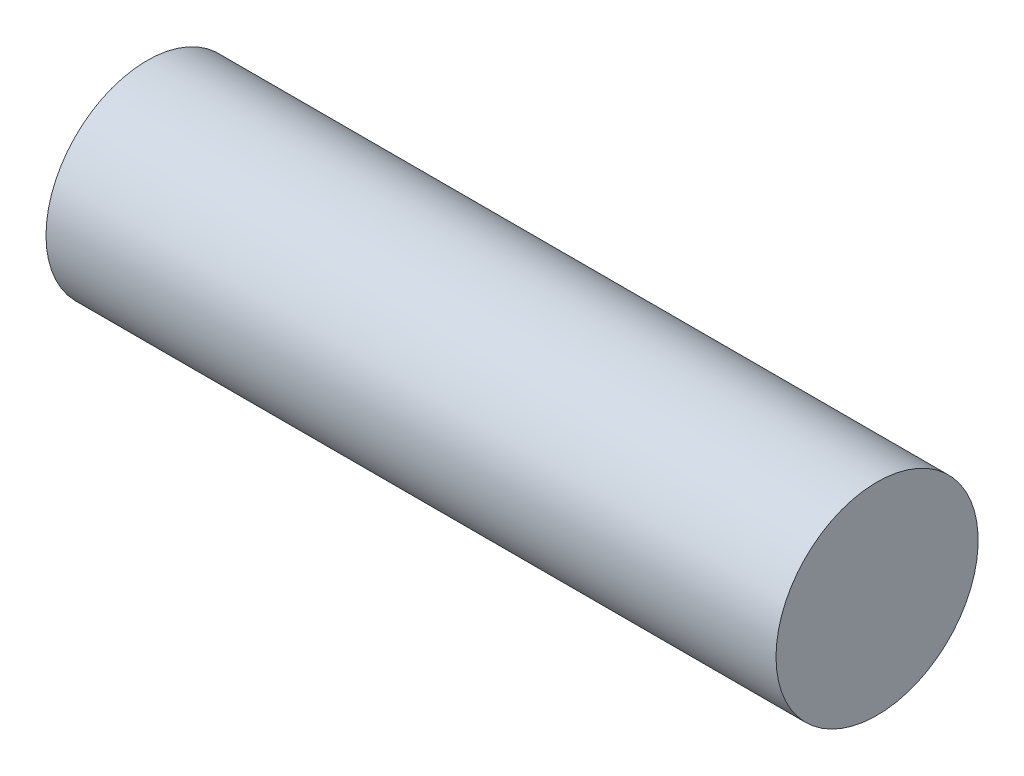
SolidWorks part; units mm, degrees
ref_plane "Front" through (0, 0, 0) normal (0, 0, 1) x (1, 0, 0)
ref_plane "Top" through (0, 0, 0) normal (0, 1, 0) x (1, 0, 0)
ref_plane "Right" through (0, 0, 0) normal (1, 0, 0) x (0, 0, -1)
sketch "Эскиз1" plane through (0, 0, 0) normal (0, 1, 0) x (1, 0, 0)
  line L0 (-39, 0) -> (43.5676, 0) construction
  line L2 (-31.6216, 0) -> (33.3784, 0)
  line L3 (-31.6216, 0) -> (-31.6216, 9)
  line L4 (-31.6216, 9) -> (33.3784, 9)
  line L5 (33.3784, 0) -> (33.3784, 9)
  dimension "D1" = 65
  dimension "D2" = 9
revolve "Повернуть1" add sketch "Эскиз1" angle 360 about L0
